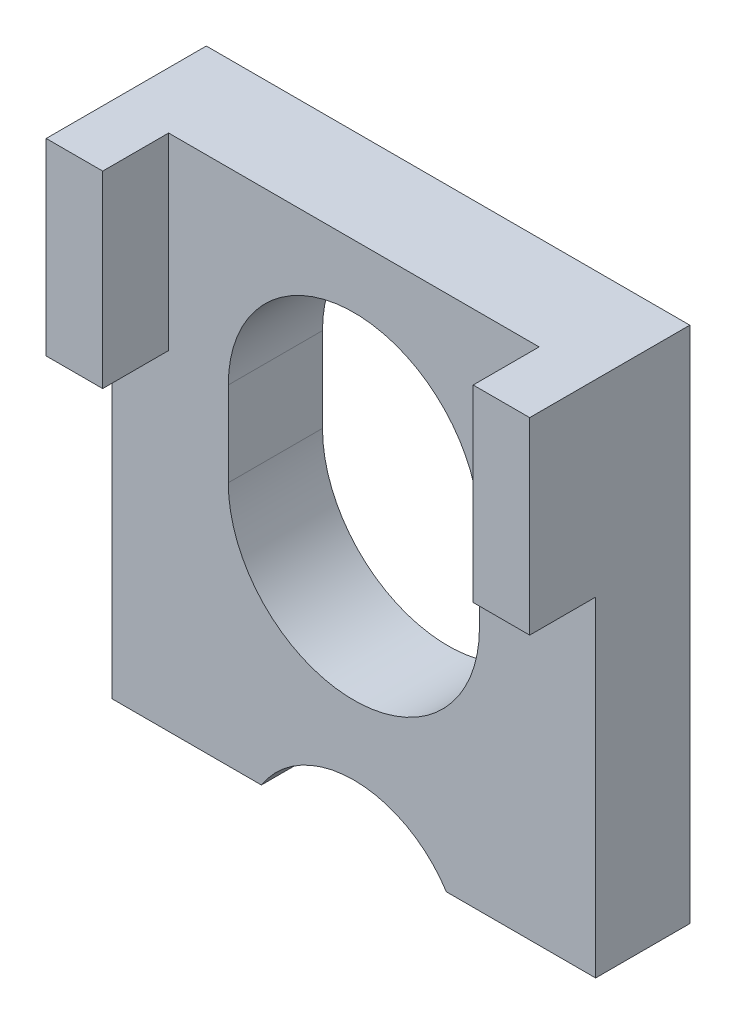
SolidWorks part; units mm, degrees
ref_plane "Спереди" through (0, 0, 0) normal (0, 0, 1) x (1, 0, 0)
ref_plane "Сверху" through (0, 0, 0) normal (0, 1, 0) x (1, 0, 0)
ref_plane "Справа" through (0, 0, 0) normal (1, 0, 0) x (0, 0, -1)
sketch "Эскиз1" plane through (0, 0, 0) normal (0, 0, 1) x (1, 0, 0)
  line L1 (-7.7, 13.7375) -> (7.7, 13.7375)
  line L5 (-7.7, 13.7375) -> (-7.7, -0.0396)
  line L6 (7.7, 13.7375) -> (7.7, -0.0396)
  line L7 (-7.7, -0.0396) -> (-7.7, -2.7696)
  line L8 (-7.7, -2.7696) -> (-2.9462, -2.7696)
  line L9 (0, 7.7375) -> (0, 5.041) construction
  line L10 (4, 7.7375) -> (4, 5.041)
  line L11 (-4, 7.7375) -> (-4, 5.041)
  line L12 (7.7, -0.0396) -> (7.7, -2.7696)
  line L13 (7.7, -2.7696) -> (2.9462, -2.7696)
  arc A0 (-2.9462, -2.7696) -> (2.9462, -2.7696) centre (0, -4.659) cw
  arc A1 (4, 7.7375) -> (-4, 7.7375) centre (0, 7.7375) ccw
  arc A2 (-4, 5.041) -> (4, 5.041) centre (0, 5.041) ccw
  point P1 (0, 6.3893)
  point P15 (0, 11.7375)
  point P16 (0, 1.041)
  dimension "D1" = 3.5
  dimension "D5" = 4
  dimension "D4" = 2.2
  dimension "D2" = 15.4
  dimension "D3" = 7.7
  dimension "D6" = 10.6965
  dimension "D7" = 2
  dimension "D8" = 7.7
extrude "Бобышка-Вытянуть1" add sketch "Эскиз1" along normal blind 3
sketch "Эскиз2" plane through (0, 0, 3) normal (0, 0, 1) x (1, 0, 0)
  line L1 (-7.7, 13.7375) -> (-5.9, 13.7375)
  line L2 (-7.7, 13.7375) -> (-7.7, 7.7375)
  line L3 (-7.7, 7.7375) -> (-5.9, 7.7375)
  line L4 (-5.9, 13.7375) -> (-5.9, 7.7375)
  line L5 (7.7, 13.7375) -> (5.9, 13.7375)
  line L6 (7.7, 13.7375) -> (7.7, 7.7375)
  line L7 (7.7, 7.7375) -> (5.9, 7.7375)
  line L8 (5.9, 13.7375) -> (5.9, 7.7375)
  dimension "D1" = 1.8
  dimension "D2" = 1.8
  dimension "D3" = 6
  dimension "D4" = 6
extrude "Бобышка-Вытянуть2" add sketch "Эскиз2" along normal blind 2.1
